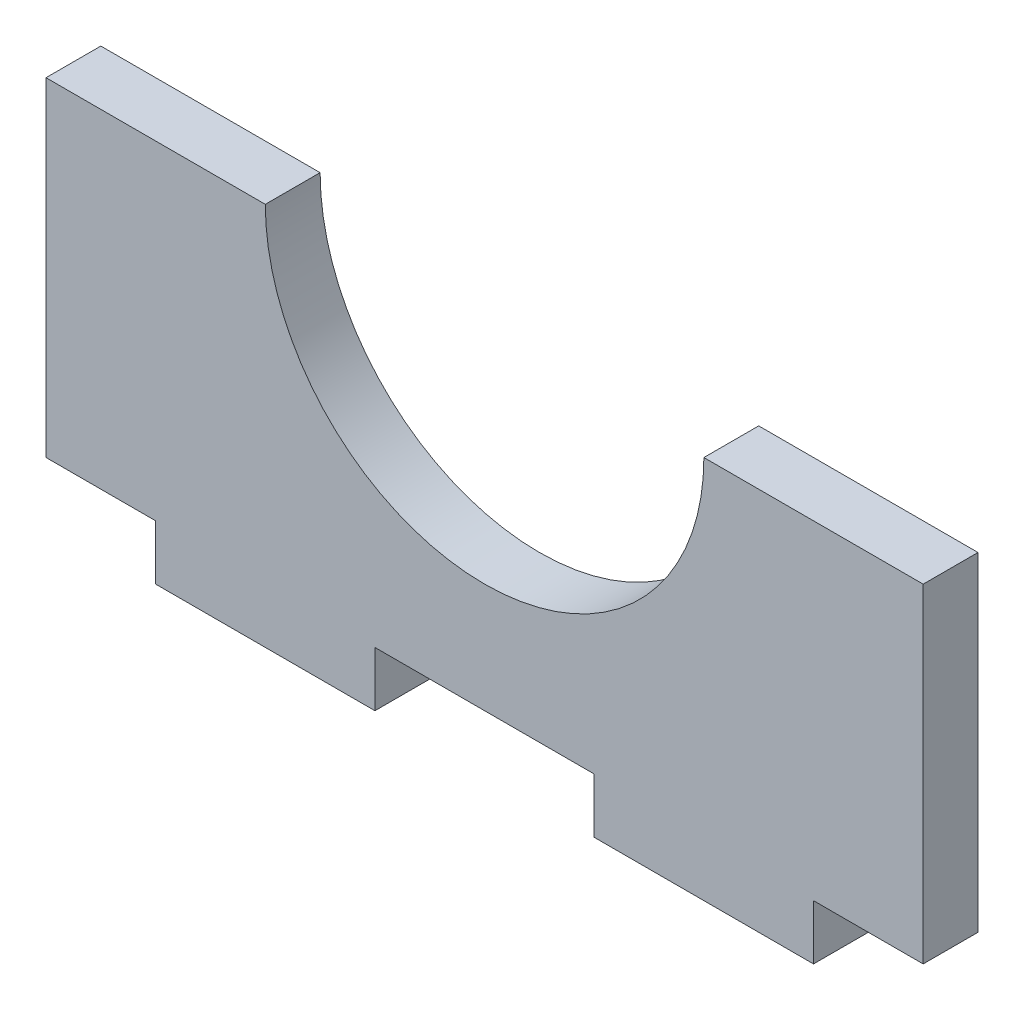
SolidWorks part; units mm, degrees
ref_plane "Front Plane" through (0, 0, 0) normal (0, 0, 1) x (1, 0, 0)
ref_plane "Top Plane" through (0, 0, 0) normal (0, 1, 0) x (1, 0, 0)
ref_plane "Right Plane" through (0, 0, 0) normal (1, 0, 0) x (0, 0, -1)
sketch "Sketch1" plane through (0, 0, 0) normal (0, 0, 1) x (1, 0, 0)
  line L0 (-12.7, 0) -> (-25.4, 0)
  line L1 (-25.4, 0) -> (-25.4, -19.05)
  line L3 (-6.35, -22.225) -> (-6.35, -19.05)
  line L4 (-6.35, -19.05) -> (6.35, -19.05)
  line L5 (6.35, -19.05) -> (6.35, -22.225)
  line L7 (25.4, -19.05) -> (25.4, 0)
  line L8 (25.4, 0) -> (12.7, 0)
  line L9 (0, 0) -> (-4.6846, -11.8044) construction
  line L10 (-25.4, -19.05) -> (-19.05, -19.05)
  line L11 (-19.05, -19.05) -> (-19.05, -22.225)
  line L12 (-19.05, -22.225) -> (-6.35, -22.225)
  line L13 (25.4, -19.05) -> (19.05, -19.05)
  line L14 (19.05, -19.05) -> (19.05, -22.225)
  line L15 (19.05, -22.225) -> (6.35, -22.225)
  arc A0 (12.7, 0) -> (-12.7, 0) centre (0, 0) cw
  dimension "D1" = 12.7
  dimension "D2" = 12.7
  dimension "D3" = 12.7
  dimension "D4" = 19.05
  dimension "D5" = 3.175
  dimension "D6" = 6.35
extrude "Boss-Extrude1" add sketch "Sketch1" along normal blind 3.175
